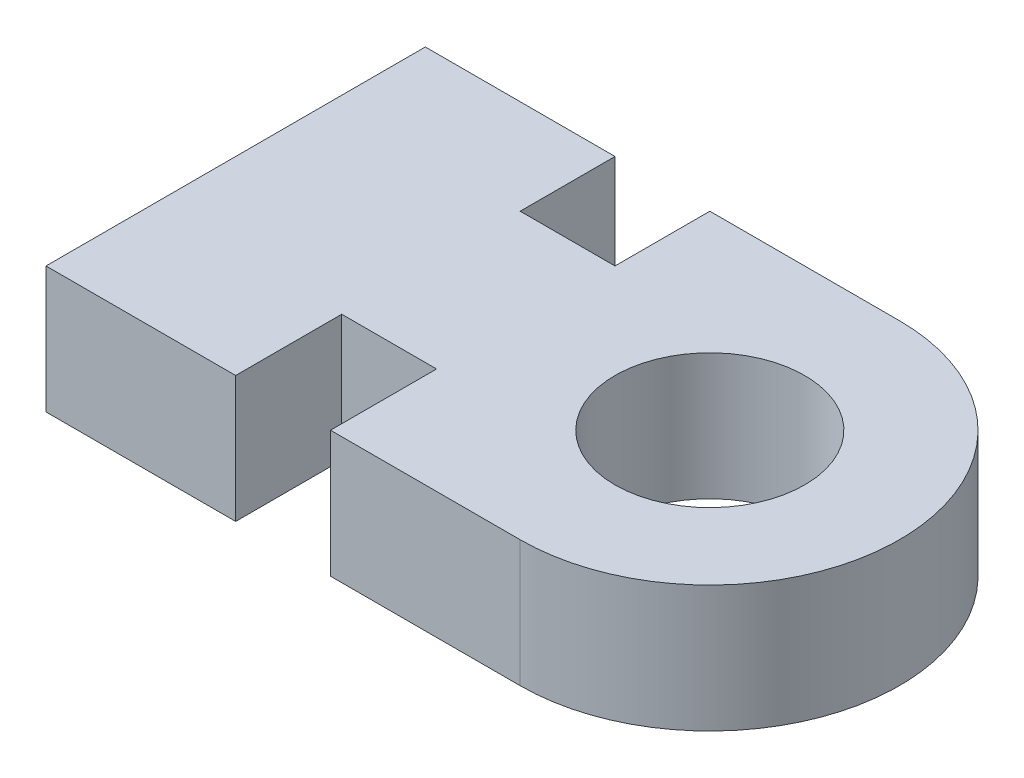
SolidWorks part; units mm, degrees
ref_plane "前基準面" through (0, 0, 0) normal (0, 0, 1) x (1, 0, 0)
ref_plane "上基準面" through (0, 0, 0) normal (0, 1, 0) x (1, 0, 0)
ref_plane "右基準面" through (0, 0, 0) normal (1, 0, 0) x (0, 0, -1)
sketch "草圖1" plane through (0, 0, 0) normal (0, 1, 0) x (1, 0, 0)
  line L0 (0, 30) -> (-30, 30)
  line L1 (-30, 30) -> (-30, 15)
  line L2 (-30, 15) -> (-45, 15)
  line L3 (-45, 15) -> (-45, 30)
  line L4 (-45, 30) -> (-75, 30)
  line L5 (-75, 30) -> (-75, -30)
  line L6 (-75, -30) -> (-45, -30)
  line L7 (-45, -30) -> (-45, -13.2229)
  line L8 (-45, -13.2229) -> (-30, -13.2229)
  line L9 (-30, -13.2229) -> (-30, -30)
  line L10 (-30, -30) -> (0, -30)
  circle A0 centre (0, 0) radius 15
  arc A1 (0, -30) -> (0, 30) centre (0, 0) ccw
  dimension "D1" = 30
  dimension "D2" = 60
  dimension "D3" = 30
  dimension "D4" = 30
  dimension "D5" = 15
  dimension "D6" = 15
  dimension "D7" = 30
  dimension "D8" = 15
extrude "填料-伸長1" add sketch "草圖1" along normal blind 20
